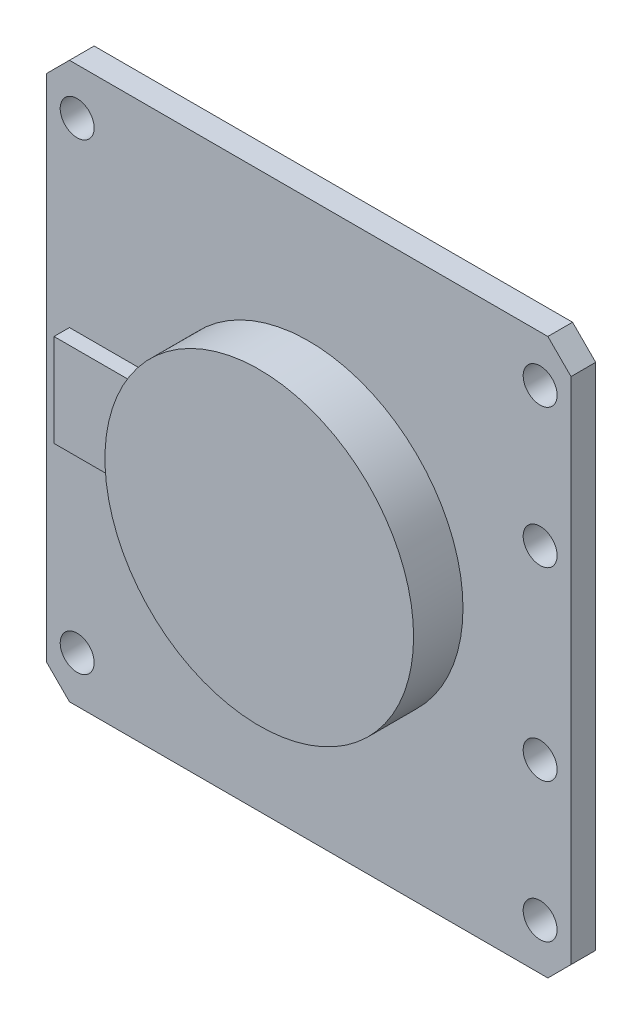
SolidWorks part; units mm, degrees
ref_plane "Front Plane" through (0, 0, 0) normal (0, 0, 1) x (1, 0, 0)
ref_plane "Top Plane" through (0, 0, 0) normal (0, 1, 0) x (1, 0, 0)
ref_plane "Right Plane" through (0, 0, 0) normal (1, 0, 0) x (0, 0, -1)
sketch "Sketch1" plane through (0, 0, 0) normal (0, 0, 1) x (1, 0, 0)
  line L1 (-17, 18) -> (17, 18)
  line L2 (-17, 18) -> (-17, -18)
  line L3 (-17, -18) -> (17, -18)
  line L4 (17, 18) -> (17, -18)
  point P4 (0, 18)
  point P6 (17, 0)
  dimension "D1" = 34
  dimension "D2" = 36
extrude "Boss-Extrude1" add sketch "Sketch1" along normal blind 1.6
chamfer "Chamfer1" distance 1.5 angle 45 4 edges at (-17, -18, 0.8) (17, -18, 0.8) (-17, 18, 0.8) (17, 18, 0.8)
sketch "Sketch2" plane through (0, 0, 1.6) normal (0, 0, 1) x (1, 0, 0)
  line L0 (0.88, 0) -> (-0.88, 0) construction
  line L1 (0, -0.88) -> (0, 0.88) construction
  circle A0 centre (-15, 15) radius 1.1
  circle A1 centre (15, 6) radius 1.1
  circle A2 centre (-15, -15) radius 1.1
  circle A3 centre (15, -15) radius 1.1
  circle A4 centre (15, 15) radius 1.1
  circle A5 centre (15, -6) radius 1.1
  dimension "D1" = 2.2
  dimension "D2" = 15
  dimension "D3" = 15
  dimension "D4" = 15
  dimension "D5" = 6
extrude "Cut-Extrude1" cut sketch "Sketch2" against normal through all
sketch "Sketch3" plane through (0, 0, 1.6) normal (0, 0, 1) x (1, 0, 0)
  circle A0 centre (0, 0) radius 10
  point P2 (0, 0)
  dimension "D1" = 20
extrude "Boss-Extrude2" add sketch "Sketch3" along normal blind 3.2
sketch "Sketch4" plane through (0, 0, 1.6) normal (0, 0, 1) x (1, 0, 0)
  line L1 (-15.5, 3) -> (-10.5, 3)
  line L2 (-15.5, 3) -> (-15.5, -3)
  line L3 (-15.5, -3) -> (-10.5, -3)
  line L4 (-10.5, 3) -> (-10.5, -3)
  point P4 (-15.5, 0)
  point P6 (-13, 3)
  dimension "D1" = 5
  dimension "D2" = 6
  dimension "D3" = 13
extrude "Boss-Extrude3" add sketch "Sketch4" along normal blind 1
